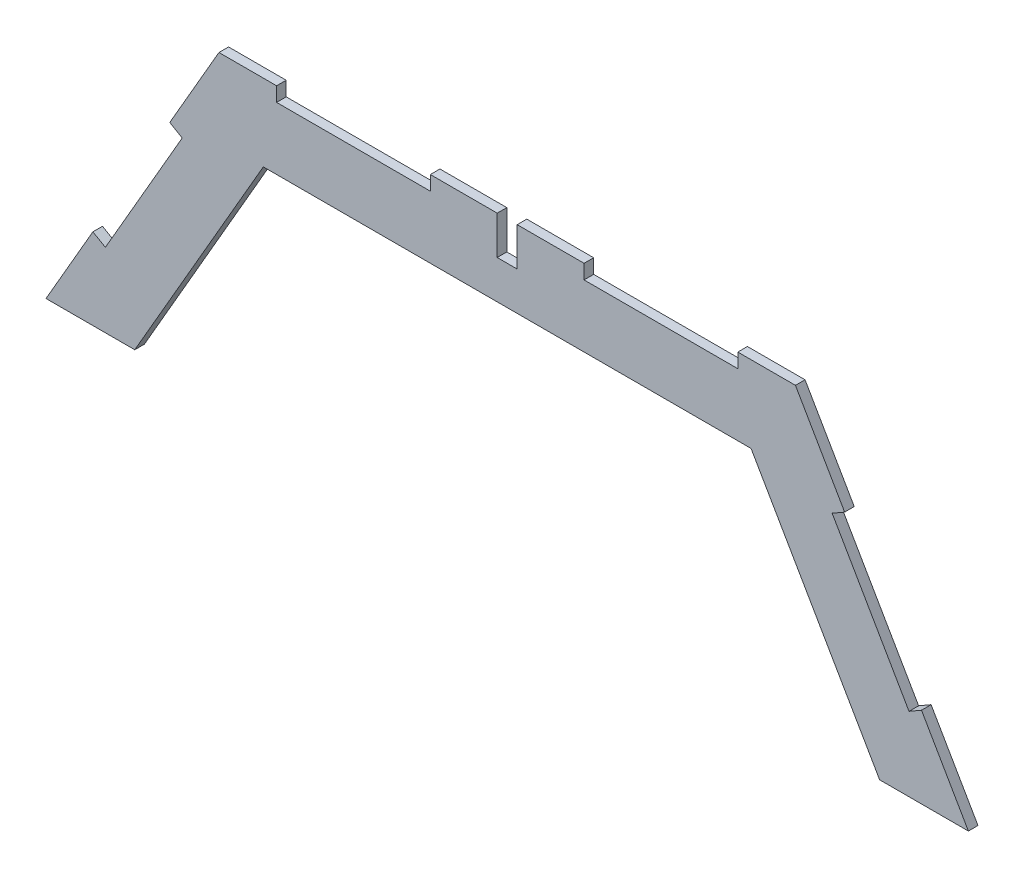
SolidWorks part; units mm, degrees
material "Balsa"
ref_plane "Front Plane" through (0, 0, 0) normal (0, 0, 1) x (1, 0, 0)
ref_plane "Top Plane" through (0, 0, 0) normal (0, 1, 0) x (1, 0, 0)
ref_plane "Right Plane" through (0, 0, 0) normal (1, 0, 0) x (0, 0, -1)
sketch "Sketch1" plane through (0, 0, 0) normal (0, 0, 1) x (1, 0, 0)
  line L0 (0, 0) -> (0, -39.8878) construction
  line L1 (0, 0) -> (83.6304, 0) construction
  line L2 (95.25, 0) -> (-95.25, 0)
  line L3 (-95.25, 0) -> (-153.67, -101.1864)
  line L4 (-153.67, -101.1864) -> (-131.673, -113.8864)
  line L5 (80.5853, -25.4) -> (-80.5853, -25.4)
  line L6 (-80.5853, -25.4) -> (-131.673, -113.8864)
  line L7 (153.67, -101.1864) -> (131.673, -113.8864)
  line L8 (95.25, 0) -> (153.67, -101.1864)
  line L9 (80.5853, -25.4) -> (131.673, -113.8864)
  point P14 (0, 0)
  point P15 (0, -25.4)
  dimension "D1" = 25.4
  dimension "D2" = 25.4
  dimension "D3" = 60
  dimension "D4" = 190.5
  dimension "D5" = 116.84
extrude "Boss-Extrude1" add sketch "Sketch1" along normal blind 3.175
sketch "Sketch2" plane through (0, 0, 3.175) normal (0, 0, 1) x (1, 0, 0)
  line L0 (0, 0) -> (0, -25.4) construction
  line L1 (95.25, 0) -> (-95.25, 0) construction
  line L2 (-80.5853, -25.4) -> (80.5853, -25.4) construction
  line L4 (-3.302, 0) -> (-3.302, -12.7)
  line L6 (-3.302, -12.7) -> (3.302, -12.7)
  line L9 (-111.506, -28.1562) -> (-136.906, -72.1503)
  line L10 (-95.25, 0) -> (-153.67, -101.1864) construction
  line L11 (-136.906, -72.1503) -> (-132.7816, -74.5316)
  line L12 (-132.7816, -74.5316) -> (-107.3816, -30.5375)
  line L13 (-107.3816, -30.5375) -> (-111.506, -28.1562)
  line L14 (-76.2, 0) -> (-76.2, -4.7625)
  line L15 (-76.2, -4.7625) -> (-25.4, -4.7625)
  line L16 (-25.4, -4.7625) -> (-25.4, 0)
  line L17 (-25.4, 0) -> (-76.2, 0)
  line L18 (25.4, 0) -> (76.2, 0)
  line L19 (25.4, -4.7625) -> (25.4, 0)
  line L20 (76.2, -4.7625) -> (25.4, -4.7625)
  line L21 (76.2, 0) -> (76.2, -4.7625)
  line L22 (107.3816, -30.5375) -> (111.506, -28.1562)
  line L23 (132.7816, -74.5316) -> (107.3816, -30.5375)
  line L24 (136.906, -72.1503) -> (132.7816, -74.5316)
  line L25 (111.506, -28.1562) -> (136.906, -72.1503)
  line L26 (-152.4, -98.9867) -> (-123.0706, -98.9867)
  line L27 (-131.673, -113.8864) -> (-80.5853, -25.4) construction
  line L28 (-123.0706, -98.9867) -> (-131.673, -113.8864)
  line L29 (-131.673, -113.8864) -> (-153.67, -101.1864)
  line L30 (-153.67, -101.1864) -> (-131.673, -113.8864) construction
  line L31 (-153.67, -101.1864) -> (-152.4, -98.9867)
  line L32 (153.67, -101.1864) -> (152.4, -98.9867)
  line L33 (131.673, -113.8864) -> (153.67, -101.1864)
  line L34 (123.0706, -98.9867) -> (131.673, -113.8864)
  line L35 (152.4, -98.9867) -> (123.0706, -98.9867)
  line L36 (3.302, -12.7) -> (3.302, 0)
  line L37 (3.302, 0) -> (-3.302, 0)
  point P10 (-124.206, -50.1533)
  point P16 (-50.8, 0)
  point P43 (0, 0)
  dimension "D1" = 57.912
  dimension "D2" = 50.8
  dimension "D3" = 4.7625
  dimension "D4" = 50.8
  dimension "D5" = 44.45
  dimension "D6" = 2.54
  dimension "D7" = 12.7
  dimension "D8" = 6.604
extrude "Cut-Extrude1" cut sketch "Sketch2" against normal through all
